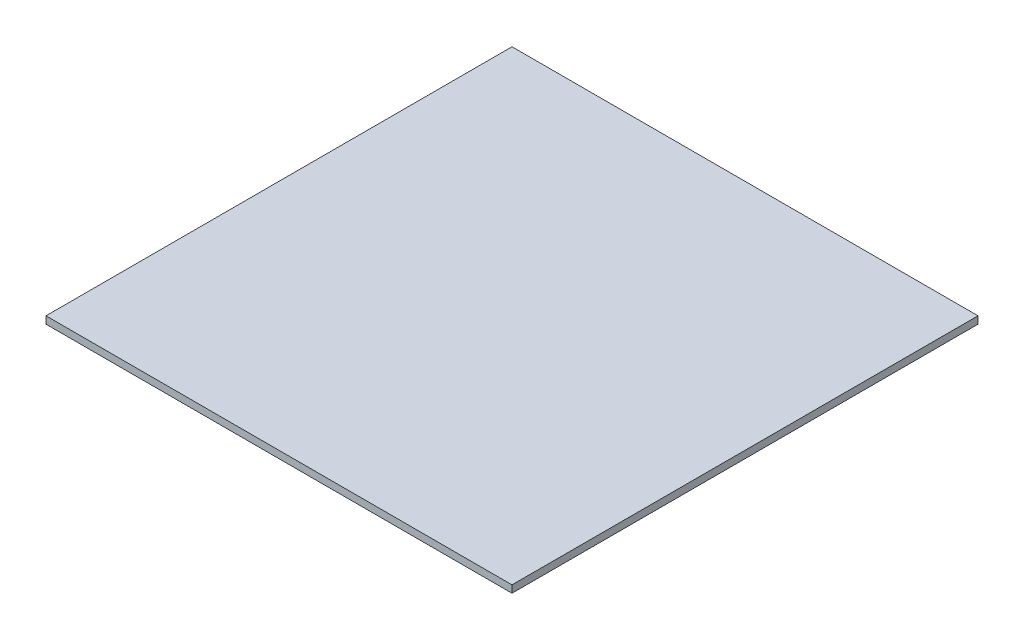
SolidWorks part; units mm, degrees
material "Balsa"
ref_plane "Front Plane" through (0, 0, 0) normal (0, 0, 1) x (1, 0, 0)
ref_plane "Top Plane" through (0, 0, 0) normal (0, 1, 0) x (1, 0, 0)
ref_plane "Right Plane" through (0, 0, 0) normal (1, 0, 0) x (0, 0, -1)
sketch "Sketch1" plane through (0, 0, 0) normal (0, 1, 0) x (1, 0, 0)
  line L1 (0, 0) -> (812.8, 0)
  line L2 (0, 0) -> (0, 812.8)
  line L3 (0, 812.8) -> (812.8, 812.8)
  line L4 (812.8, 0) -> (812.8, 812.8)
  dimension "D1" = 812.8
  dimension "D2" = 812.8
extrude "Boss-Extrude1" add sketch "Sketch1" along normal blind 12.7
